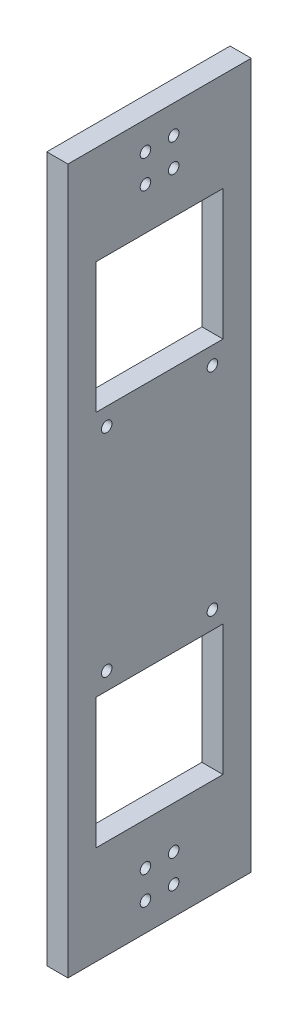
SolidWorks part; units mm, degrees
material "ABS"
ref_plane "Front Plane" through (0, 0, 0) normal (0, 0, 1) x (1, 0, 0)
ref_plane "Top Plane" through (0, 0, 0) normal (0, 1, 0) x (1, 0, 0)
ref_plane "Right Plane" through (0, 0, 0) normal (1, 0, 0) x (0, 0, -1)
ref_plane "P_yoke_184_x" through (-132.7, 0, 0) normal (1, 0, 0) x (0, 0, -1)
sketch "Sketch1" plane through (-132.7, 0, 0) normal (1, 0, 0) x (0, 0, -1)
  line L1 (-26, -100) -> (26, -100)
  line L2 (-26, -100) -> (-26, 100)
  line L3 (-26, 100) -> (26, 100)
  line L4 (26, -100) -> (26, 100)
extrude "Boss-Extrude1" add sketch "Sketch1" along normal blind 6
ref_plane "P_yk_holes" through (-132.7, 0, 0) normal (1, 0, 0) x (0, 0, -1)
sketch "Sketch2" plane through (-132.7, 0, 0) normal (1, 0, 0) x (0, 0, -1)
  circle A0 centre (-4, 84) radius 1.5
extrude "Cut-Extrude2" cut sketch "Sketch2" along normal blind 6
sketch "Sketch3" plane through (-132.7, 0, 0) normal (1, 0, 0) x (0, 0, -1)
  circle A0 centre (4, 84) radius 1.5
extrude "Cut-Extrude4" cut sketch "Sketch3" along normal blind 6
sketch "Sketch4" plane through (-132.7, 0, 0) normal (1, 0, 0) x (0, 0, -1)
  circle A0 centre (-4, 92) radius 1.5
extrude "Cut-Extrude6" cut sketch "Sketch4" along normal blind 6
sketch "Sketch5" plane through (-132.7, 0, 0) normal (1, 0, 0) x (0, 0, -1)
  circle A0 centre (4, 92) radius 1.5
extrude "Cut-Extrude8" cut sketch "Sketch5" along normal blind 6
sketch "Sketch6" plane through (-132.7, 0, 0) normal (1, 0, 0) x (0, 0, -1)
  circle A0 centre (-4, -92) radius 1.5
extrude "Cut-Extrude10" cut sketch "Sketch6" along normal blind 6
sketch "Sketch7" plane through (-132.7, 0, 0) normal (1, 0, 0) x (0, 0, -1)
  circle A0 centre (4, -92) radius 1.5
extrude "Cut-Extrude12" cut sketch "Sketch7" along normal blind 6
sketch "Sketch8" plane through (-132.7, 0, 0) normal (1, 0, 0) x (0, 0, -1)
  circle A0 centre (-4, -84) radius 1.5
extrude "Cut-Extrude14" cut sketch "Sketch8" along normal blind 6
sketch "Sketch9" plane through (-132.7, 0, 0) normal (1, 0, 0) x (0, 0, -1)
  circle A0 centre (4, -84) radius 1.5
extrude "Cut-Extrude16" cut sketch "Sketch9" along normal blind 6
sketch "Sketch10" plane through (-132.7, 0, 0) normal (1, 0, 0) x (0, 0, -1)
  circle A0 centre (-15, -30) radius 1.5
extrude "Cut-Extrude18" cut sketch "Sketch10" along normal blind 6
sketch "Sketch11" plane through (-132.7, 0, 0) normal (1, 0, 0) x (0, 0, -1)
  circle A0 centre (15, -30) radius 1.5
extrude "Cut-Extrude20" cut sketch "Sketch11" along normal blind 6
sketch "Sketch12" plane through (-132.7, 0, 0) normal (1, 0, 0) x (0, 0, -1)
  circle A0 centre (-15, 30) radius 1.5
extrude "Cut-Extrude22" cut sketch "Sketch12" along normal blind 6
sketch "Sketch13" plane through (-132.7, 0, 0) normal (1, 0, 0) x (0, 0, -1)
  circle A0 centre (15, 30) radius 1.5
extrude "Cut-Extrude24" cut sketch "Sketch13" along normal blind 6
ref_plane "P_winp1" through (-132.7, 0, 0) normal (1, 0, 0) x (0, 0, -1)
sketch "Sketch14" plane through (-132.7, 0, 0) normal (1, 0, 0) x (0, 0, -1)
  line L1 (-18, 35) -> (18, 35)
  line L2 (-18, 35) -> (-18, 72)
  line L3 (-18, 72) -> (18, 72)
  line L4 (18, 35) -> (18, 72)
extrude "Cut-Extrude26" cut sketch "Sketch14" along normal blind 6
ref_plane "P_winm1" through (-132.7, 0, 0) normal (1, 0, 0) x (0, 0, -1)
sketch "Sketch15" plane through (-132.7, 0, 0) normal (1, 0, 0) x (0, 0, -1)
  line L1 (-18, -72) -> (18, -72)
  line L2 (-18, -72) -> (-18, -35)
  line L3 (-18, -35) -> (18, -35)
  line L4 (18, -72) -> (18, -35)
extrude "Cut-Extrude28" cut sketch "Sketch15" along normal blind 6
